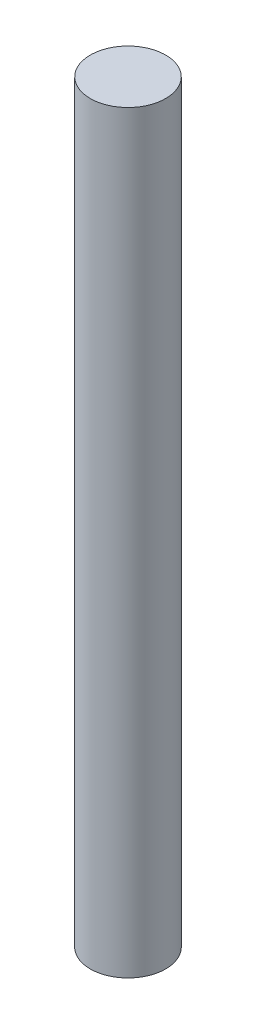
SolidWorks part; units mm, degrees
ref_plane "Front Plane" through (0, 0, 0) normal (0, 0, 1) x (1, 0, 0)
ref_plane "Top Plane" through (0, 0, 0) normal (0, 1, 0) x (1, 0, 0)
ref_plane "Right Plane" through (0, 0, 0) normal (1, 0, 0) x (0, 0, -1)
sketch "Sketch1" plane through (0, 0, 0) normal (0, 1, 0) x (1, 0, 0)
  circle A0 centre (0, 0) radius 8.5
  dimension "D1" = 17
extrude "Boss-Extrude1" add sketch "Sketch1" along normal blind 170
